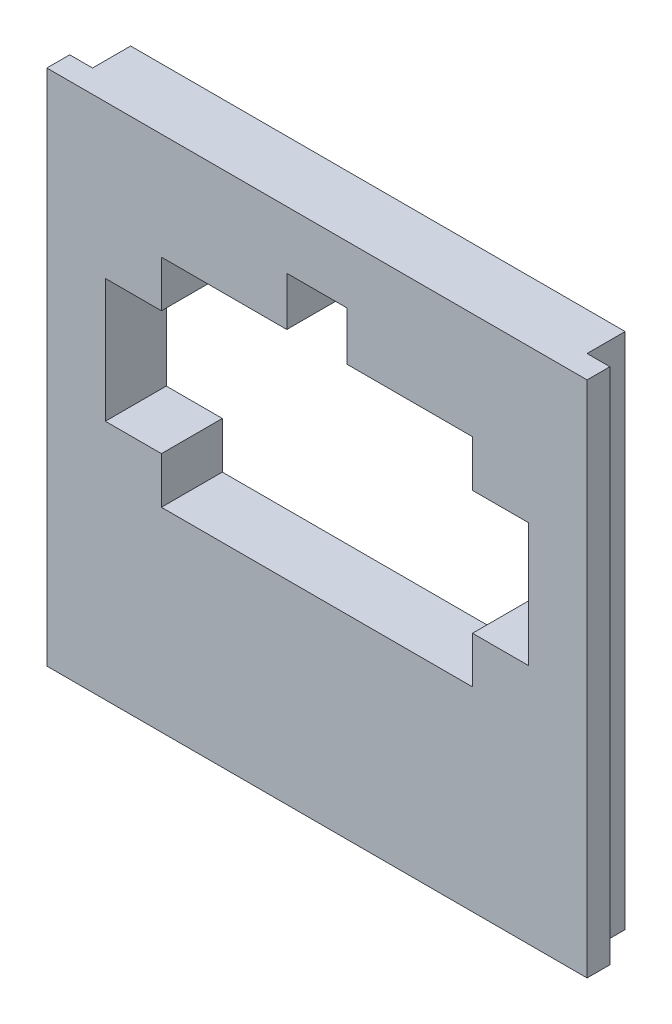
SolidWorks part; units mm, degrees
material "PET"
ref_plane "Front Plane" through (0, 0, 0) normal (0, 0, 1) x (1, 0, 0)
ref_plane "Top Plane" through (0, 0, 0) normal (0, 1, 0) x (1, 0, 0)
ref_plane "Right Plane" through (0, 0, 0) normal (1, 0, 0) x (0, 0, -1)
sketch "Sketch1" plane through (0, 0, 0) normal (0, 0, 1) x (1, 0, 0)
  line L1 (-5.7029, 6.1497) -> (10.5271, 6.1497)
  line L2 (-5.7029, 6.1497) -> (-5.7029, -10.8503)
  line L3 (-5.7029, -10.8503) -> (10.5271, -10.8503)
  line L4 (10.5271, 6.1497) -> (10.5271, -10.8503)
  dimension "D1" = 17
  dimension "D2" = 16.23
extrude "Boss-Extrude1" add sketch "Sketch1" along normal blind 2
sketch "Sketch2" plane through (10.5271, 0, 0) normal (1, 0, 0) x (0, 0, -1)
  line L0 (-2, -10.8503) -> (0, -10.8503) construction
  line L1 (-2, 6.1497) -> (-1.251, 6.1497)
  line L2 (-2, 6.1497) -> (-2, -10.8503)
  line L3 (-2, -10.8503) -> (-1.251, -10.8503)
  line L4 (-1.251, 6.1497) -> (-1.251, -10.8503)
  dimension "D1" = 0.749
extrude "Boss-Extrude2" add sketch "Sketch2" along normal blind 0.75
sketch "Sketch3" plane through (-5.7029, 0, 0) normal (-1, 0, 0) x (0, 0, 1)
  line L0 (2, -10.8503) -> (0, -10.8503) construction
  line L1 (2, 6.1497) -> (1.25, 6.1497)
  line L2 (2, 6.1497) -> (2, -10.8503)
  line L3 (2, -10.8503) -> (1.25, -10.8503)
  line L4 (1.25, 6.1497) -> (1.25, -10.8503)
  dimension "D1" = 0.75
extrude "Boss-Extrude4" add sketch "Sketch3" along normal blind 0.75
sketch "Sketch4" plane through (0, 0, 0) normal (0, 0, -1) x (-1, 0, 0)
  line L0 (-2.4121, 6.1497) -> (-2.4121, -10.8503) construction
  line L1 (-10.5271, 6.1497) -> (5.7029, 6.1497) construction
  line L2 (5.7029, -10.8503) -> (-10.5271, -10.8503) construction
  line L3 (-10.5271, -2.3503) -> (5.7029, -2.3503) construction
  line L4 (-10.5271, -10.8503) -> (-10.5271, 6.1497) construction
  line L5 (5.7029, 6.1497) -> (5.7029, -10.8503) construction
  line L6 (-7.5171, 2.654) -> (-3.4021, 2.654)
  line L7 (-7.5171, -4.456) -> (2.6929, -4.456)
  line L8 (-3.4021, 4.254) -> (-1.4221, 4.254)
  line L9 (-3.4021, 4.254) -> (-3.4021, 2.654)
  line L10 (-1.4221, 4.254) -> (-1.4221, 2.654)
  line L11 (-1.4221, 2.654) -> (2.6929, 2.654)
  line L12 (2.6929, 2.654) -> (2.6929, 1.129)
  line L13 (2.6929, 1.129) -> (4.5329, 1.129)
  line L14 (2.6929, -2.931) -> (4.5329, -2.931)
  line L15 (4.5329, 1.129) -> (4.5329, -2.931)
  line L16 (-9.3571, 1.129) -> (-7.5171, 1.129)
  line L17 (-9.3571, 1.129) -> (-9.3571, -2.931)
  line L18 (-9.3571, -2.931) -> (-7.5171, -2.931)
  line L19 (2.6929, -4.456) -> (2.6929, -2.931)
  line L20 (-7.5171, -4.456) -> (-7.5171, -2.931)
  line L21 (-7.5171, 2.654) -> (-7.5171, 1.129)
  dimension "D1" = 4.06
  dimension "D2" = 10.21
  dimension "D3" = 13.89
  dimension "D4" = 1.98
  dimension "D5" = 8.71
  dimension "D6" = 7.11
extrude "Cut-Extrude1" cut sketch "Sketch4" against normal through all
sketch "Sketch6" plane through (0, 0, 0) normal (0, 0, -1) x (-1, 0, 0)
  line L0 (-2.4121, -4.456) -> (-2.4121, -10.8503) construction
  line L1 (-7.5171, -4.456) -> (2.6929, -4.456) construction
  line L2 (5.7029, -10.8503) -> (-10.5271, -10.8503) construction
  line L3 (-5.4121, -10.8503) -> (0.5879, -10.8503)
  arc A0 (-5.4121, -10.8503) -> (0.5879, -10.8503) centre (-2.4121, -10.8503) cw
extrude "Cut-Extrude3" cut sketch "Sketch6" against normal blind 0.5
